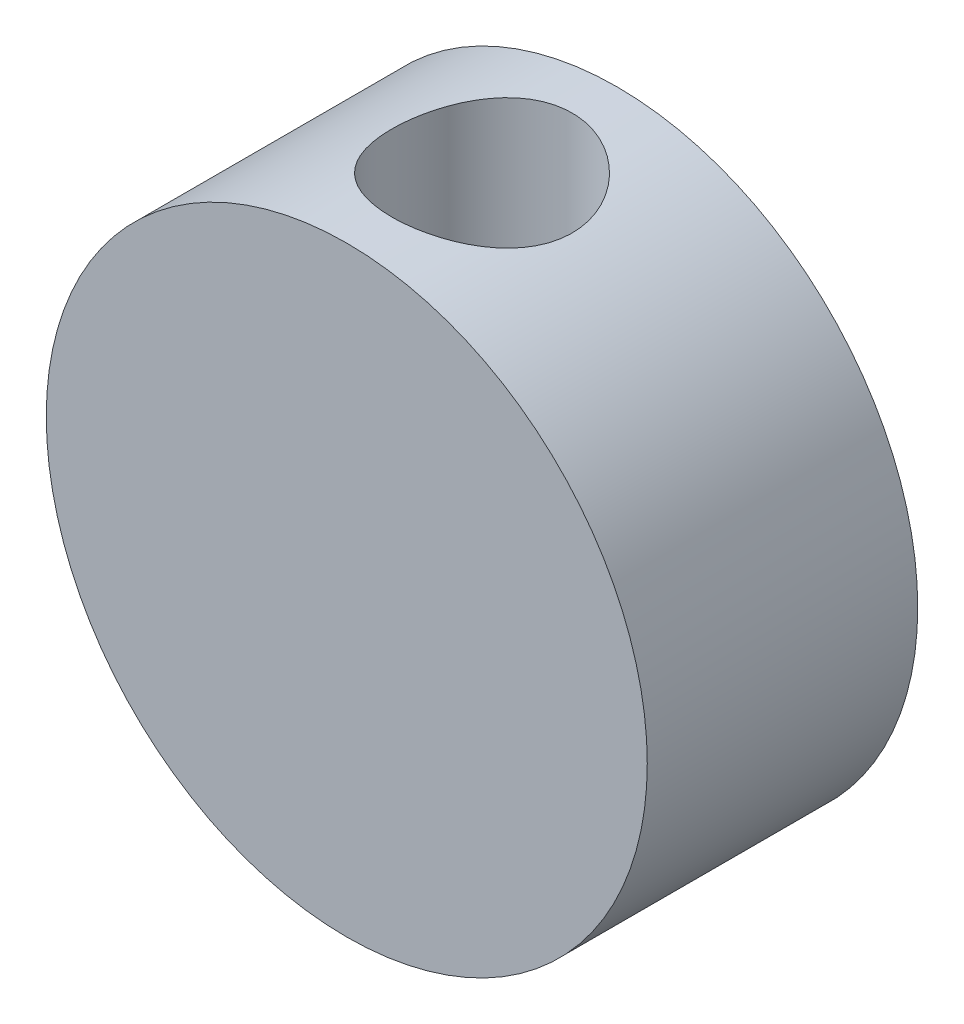
SolidWorks part; units mm, degrees
ref_plane "Front" through (0, 0, 0) normal (0, 0, 1) x (1, 0, 0)
ref_plane "Top" through (0, 0, 0) normal (0, 1, 0) x (1, 0, 0)
ref_plane "Right" through (0, 0, 0) normal (1, 0, 0) x (0, 0, -1)
sketch "草图1" plane through (0, 0, 0) normal (0, 0, 1) x (1, 0, 0)
  circle A0 centre (0, 0) radius 5
extrude "凸台-拉伸1" add sketch "草图1" along normal blind 4.5
sketch "草图2" plane through (0, 0, 0) normal (0, 1, 0) x (1, 0, 0)
  line L0 (-9.0158, 0) -> (8.419, 0) construction
  line L1 (-5, -4.5) -> (9.2986, -4.5) construction
  line L2 (0, -7.1035) -> (0, 6.3418) construction
  circle A0 centre (0, -2.25) radius 1.5
  dimension "D1" = 3
  dimension "D2" = 2.25
extrude "切除-拉伸1" cut sketch "草图2" against normal mid plane 10
